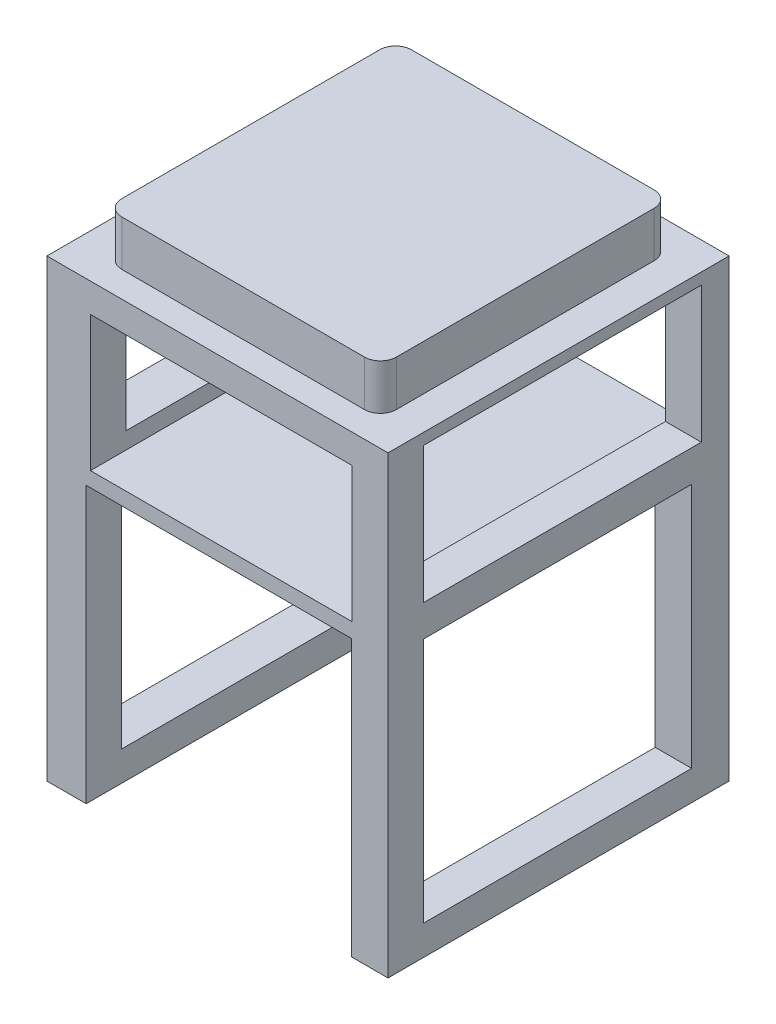
SolidWorks part; units mm, degrees
ref_plane "Alzado" through (0, 0, 0) normal (0, 0, 1) x (1, 0, 0)
ref_plane "Planta" through (0, 0, 0) normal (0, 1, 0) x (1, 0, 0)
ref_plane "Vista lateral" through (0, 0, 0) normal (1, 0, 0) x (0, 0, -1)
sketch "Croquis1" plane through (0, 0, 0) normal (0, 1, 0) x (1, 0, 0)
  line L1 (-750, 750) -> (750, 750)
  line L2 (-750, 750) -> (-750, -750)
  line L3 (-750, -750) -> (750, -750)
  line L4 (750, 750) -> (750, -750)
  line L5 (-750, 750) -> (750, -750) construction
  line L6 (-750, -750) -> (750, 750) construction
  point P0 (0, 0)
  dimension "D1" = 1500
  dimension "D2" = 1500
extrude "Saliente-Extruir1" add sketch "Croquis1" along normal blind 2000
sketch "Croquis2" plane through (0, 0, 750) normal (0, 0, 1) x (1, 0, 0)
  line L1 (-558.5513, 1873.0061) -> (592.4015, 1873.0061)
  line L2 (-558.5513, 1873.0061) -> (-558.5513, 1278.1464)
  line L3 (-558.5513, 1278.1464) -> (592.4015, 1278.1464)
  line L4 (592.4015, 1873.0061) -> (592.4015, 1278.1464)
  line L5 (-558.5513, 1873.0061) -> (592.4015, 1278.1464) construction
  line L6 (-558.5513, 1278.1464) -> (592.4015, 1873.0061) construction
  point P0 (16.9251, 1575.5762)
  point P5 (606.9912, 1283.9228)
  point P6 (-558.5513, 1278.1464)
  point P7 (592.4015, 1873.0061)
extrude "Cortar-Extruir1" cut sketch "Croquis2" against normal blind 2000
sketch "Croquis3" plane through (750, 0, 0) normal (1, 0, 0) x (0, 0, -1)
  line L0 (-750, 1264.0978) -> (750, 1264.0978)
  line L1 (-750, 2000) -> (-750, 0) construction
  line L2 (750, 2000) -> (750, 0) construction
  line L4 (-594.0713, 1950.0927) -> (627.7774, 1950.0927)
  line L5 (-594.0713, 1950.0927) -> (-594.0713, 1351.8082)
  line L6 (-594.0713, 1351.8082) -> (627.7774, 1351.8082)
  line L7 (627.7774, 1950.0927) -> (627.7774, 1351.8082)
  line L8 (-594.0713, 1950.0927) -> (627.7774, 1351.8082) construction
  line L9 (-594.0713, 1351.8082) -> (627.7774, 1950.0927) construction
  point P6 (16.8531, 1650.9504)
  point P11 (-703.6163, 1945.8794)
  point P12 (627.7774, 1351.8082)
  point P13 (-594.0713, 1950.0927)
extrude "Cortar-Extruir2" cut sketch "Croquis3" against normal blind 2000 contours L7 L4 L5 L6
sketch "Croquis6" plane through (750, 0, 0) normal (1, 0, 0) x (0, 0, -1)
  line L1 (-594.0915, 1212.7702) -> (585.3548, 1212.7702)
  line L2 (-594.0915, 1212.7702) -> (-594.0915, 130.7044)
  line L3 (-594.0915, 130.7044) -> (585.3548, 130.7044)
  line L4 (585.3548, 1212.7702) -> (585.3548, 130.7044)
  line L5 (-594.0915, 1212.7702) -> (585.3548, 130.7044) construction
  line L6 (-594.0915, 130.7044) -> (585.3548, 1212.7702) construction
  point P0 (-4.3683, 671.7373)
  point P5 (585.3548, 113.2311)
  point P6 (-594.0915, 130.7044)
extrude "Cortar-Extruir5" cut sketch "Croquis6" against normal blind 2000
sketch "Croquis7" plane through (0, 0, 750) normal (0, 0, 1) x (1, 0, 0)
  line L0 (-750, 0) -> (750, 0) construction
  line L1 (-577.2182, 1212.7702) -> (589.858, 1212.7702)
  line L2 (-577.2182, 1212.7702) -> (-577.2182, 0)
  line L3 (-577.2182, 0) -> (589.858, 0)
  line L4 (589.858, 1212.7702) -> (589.858, 0)
  line L5 (-577.2182, 1212.7702) -> (589.858, 0) construction
  line L6 (-577.2182, 0) -> (589.858, 1212.7702) construction
  point P0 (6.3199, 606.3851)
  point P7 (589.858, 1195.9171)
  point P8 (-577.2182, 1212.7702)
extrude "Cortar-Extruir6" cut sketch "Croquis7" against normal blind 2000
sketch "Croquis10" plane through (0, 2000, 0) normal (0, 1, 0) x (1, 0, 0)
  line L1 (-533.5511, 636.7306) -> (533.5511, 636.7306)
  line L2 (-603.5511, 566.7306) -> (-603.5511, -566.7306)
  line L3 (-533.5511, -636.7306) -> (533.5511, -636.7306)
  line L4 (603.5511, 566.7306) -> (603.5511, -566.7306)
  line L5 (-603.5511, 636.7306) -> (603.5511, -636.7306) construction
  line L6 (-603.5511, -636.7306) -> (603.5511, 636.7306) construction
  arc A0 (533.5511, 636.7306) -> (603.5511, 566.7306) centre (533.5511, 566.7306) cw
  arc A1 (533.5511, -636.7306) -> (603.5511, -566.7306) centre (533.5511, -566.7306) ccw
  arc A2 (-603.5511, -566.7306) -> (-533.5511, -636.7306) centre (-533.5511, -566.7306) ccw
  arc A3 (-533.5511, 636.7306) -> (-603.5511, 566.7306) centre (-533.5511, 566.7306) ccw
  point P0 (0, 0)
  dimension "D1" = 70
extrude "Saliente-Extruir2" add sketch "Croquis10" along normal blind 200
